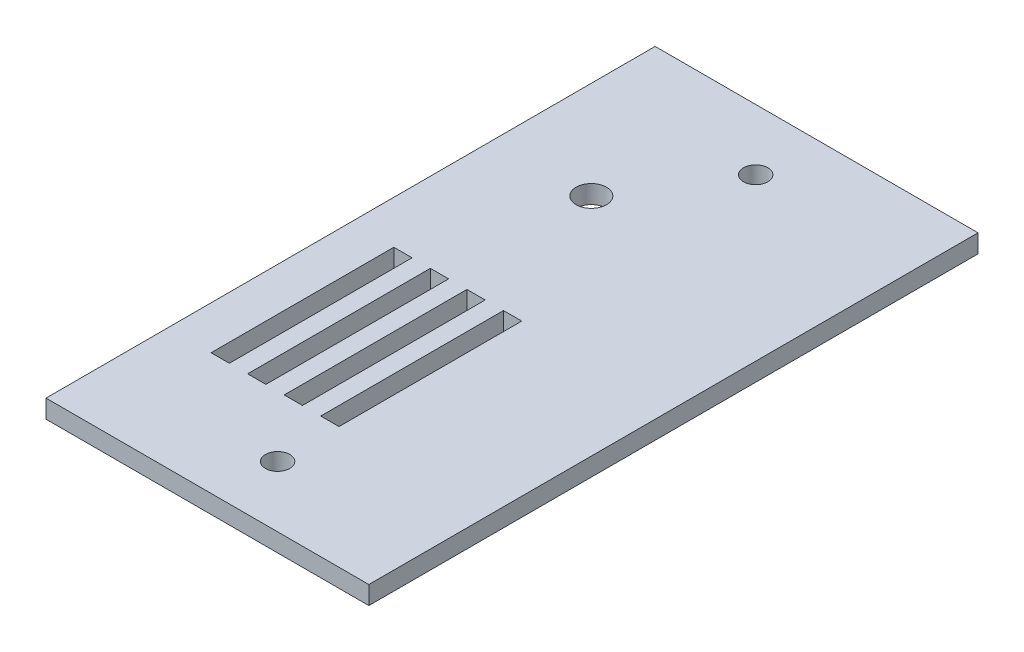
SolidWorks part; units mm, degrees
ref_plane "Plano frontal" through (0, 0, 0) normal (0, 0, 1) x (1, 0, 0)
ref_plane "Plano superior" through (0, 0, 0) normal (0, 1, 0) x (1, 0, 0)
ref_plane "Plano direito" through (0, 0, 0) normal (1, 0, 0) x (0, 0, -1)
sketch "Esboço2" plane through (0, 0, 0) normal (0, 1, 0) x (1, 0, 0)
  line L1 (-53.0204, 100) -> (-0.0204, 100)
  line L2 (-53.0204, 100) -> (-53.0204, 0)
  line L3 (-53.0204, 0) -> (-0.0204, 0)
  line L4 (-0.0204, 100) -> (-0.0204, 0)
extrude "Ressalto-extrusão1" add sketch "Esboço2" along normal blind 3 contours L1 L4 L3 L2
sketch "Esboço3" plane through (0, 3, 0) normal (0, 1, 0) x (1, 0, 0)
  circle A0 centre (-25, 10) radius 2
extrude "Corte-extrusão1" cut sketch "Esboço3" against normal blind 10 contours A0
sketch "Esboço4" plane through (0, 3, 0) normal (0, 1, 0) x (1, 0, 0)
  circle A0 centre (-37, 73.5) radius 2.5
extrude "Corte-extrusão3" cut sketch "Esboço4" against normal blind 10 contours A0
sketch "Esboço5" plane through (0, 3, 0) normal (0, 1, 0) x (1, 0, 0)
  circle A0 centre (-26.5204, 90) radius 2
extrude "Corte-extrusão4" cut sketch "Esboço5" against normal blind 10
sketch "Esboço6" plane through (0, 3, 0) normal (0, 1, 0) x (1, 0, 0)
  line L0 (-45.9195, 0) -> (-45.9195, 20) construction
  line L1 (-53.0204, 0) -> (-0.0204, 0) construction
  line L2 (-42.9195, 20) -> (-39.9195, 20) construction
  line L3 (-45.9195, 20) -> (-42.9195, 20)
  line L4 (-45.9195, 20) -> (-45.9195, 50)
  line L5 (-45.9195, 50) -> (-42.9195, 50)
  line L6 (-42.9195, 20) -> (-42.9195, 50)
  line L7 (-36.9195, 50) -> (-33.9195, 50) construction
  line L8 (-39.9195, 20) -> (-36.9195, 20)
  line L9 (-39.9195, 20) -> (-39.9195, 50)
  line L10 (-39.9195, 50) -> (-36.9195, 50)
  line L11 (-36.9195, 20) -> (-36.9195, 50)
  line L12 (-30.9195, 20) -> (-27.9195, 20) construction
  line L13 (-33.9195, 50) -> (-30.9195, 50)
  line L14 (-33.9195, 50) -> (-33.9195, 20)
  line L15 (-33.9195, 20) -> (-30.9195, 20)
  line L16 (-30.9195, 50) -> (-30.9195, 20)
  line L19 (-27.9195, 20) -> (-24.9195, 20)
  line L20 (-27.9195, 20) -> (-27.9195, 50)
  line L21 (-27.9195, 50) -> (-24.9195, 50)
  line L22 (-24.9195, 20) -> (-24.9195, 50)
  dimension "D1" = 20
  dimension "D2" = 30
  dimension "D3" = 3
  dimension "D4" = 3
  dimension "D5" = 3
  dimension "D6" = 3
  dimension "D7" = 3
  dimension "D8" = 30
  dimension "D9" = 3
  dimension "D10" = 3
extrude "Corte-extrusão8" cut sketch "Esboço6" against normal blind 10
